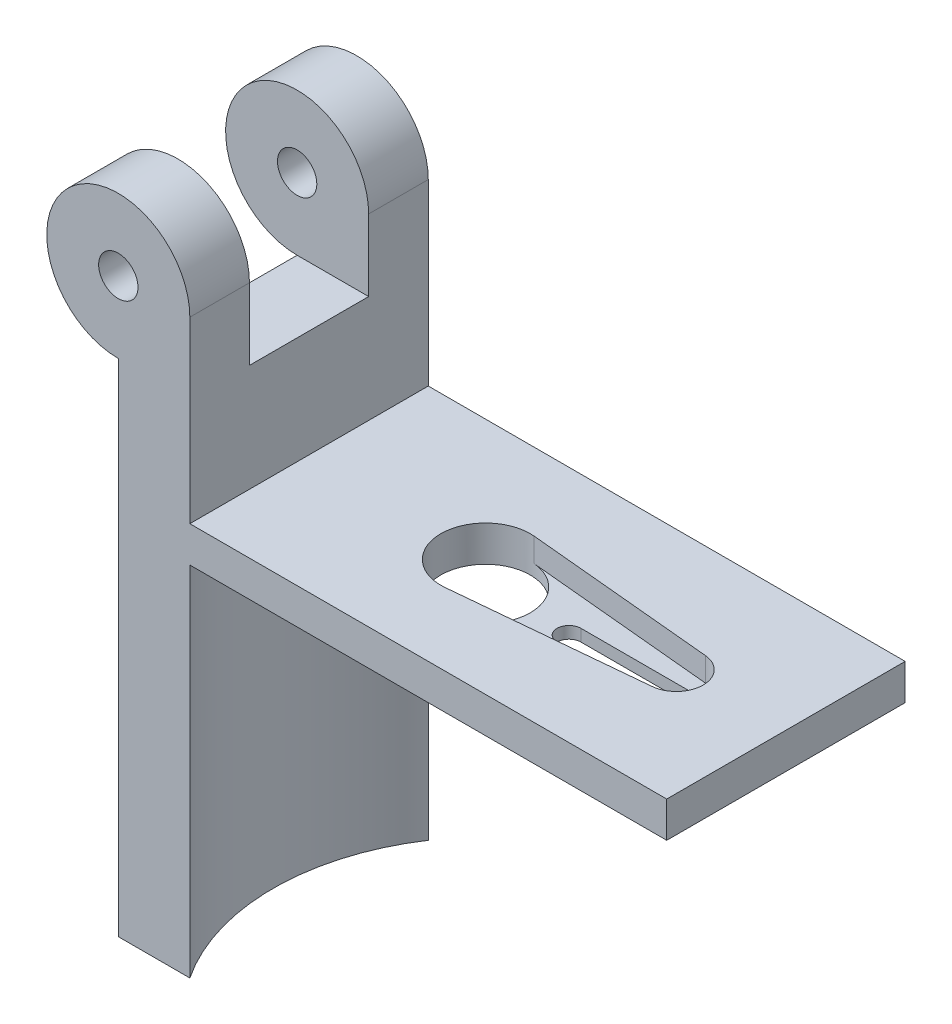
SolidWorks part; units mm, degrees
ref_plane "前视基准面" through (0, 0, 0) normal (0, 0, 1) x (1, 0, 0)
ref_plane "上视基准面" through (0, 0, 0) normal (0, 1, 0) x (1, 0, 0)
ref_plane "右视基准面" through (0, 0, 0) normal (1, 0, 0) x (0, 0, -1)
sketch "草图1" plane through (0, 0, 0) normal (0, 0, 1) x (1, 0, 0)
  line L1 (0, 0) -> (6, 0)
  line L2 (0, 0) -> (0, -48)
  line L3 (0, -48) -> (6, -48)
  line L4 (6, 0) -> (6, -48)
  line L5 (6, -15) -> (46, -15)
  line L6 (6, -15) -> (6, -18)
  line L7 (6, -18) -> (46, -18)
  line L8 (46, -15) -> (46, -18)
  circle A0 centre (0, 0) radius 1.65
  circle A1 centre (0, 0) radius 6
  dimension "D1" = 3.3
  dimension "D2" = 12
  dimension "D3" = 3
  dimension "D4" = 40
  dimension "D5" = 15
  dimension "D6" = 30
extrude "凸台-拉伸1" add sketch "草图1" along normal blind 20 contours L1 A1 L2 A0 | L2 A1 L1 A0 | A1 L2 L3 L4 | L8 L5 L4 L7
sketch "草图2" plane through (0, -15, 0) normal (0, 1, 0) x (1, 0, 0)
  line L0 (37.2109, -7.9566) -> (21.3516, -6.4632)
  line L1 (37.2109, -12.4368) -> (21.3516, -13.9302)
  line L2 (6, -20) -> (6, 0) construction
  circle A0 centre (37, -10.1967) radius 2.25
  circle A1 centre (21, -10.1967) radius 3.75
  point P8 (26.7105, -11.1863)
  point P9 (28.0646, -10.1967)
  dimension "D1" = 4.5
  dimension "D2" = 7.5
  dimension "D3" = 16
  dimension "D4" = 15
extrude "切除-拉伸1" cut sketch "草图2" against normal blind 2 contours A1 L1 A0 L0 | A0
sketch "草图3" plane through (0, -15, 0) normal (0, 1, 0) x (1, 0, 0)
  circle A0 centre (21, -10.1967) radius 3.75
extrude "切除-拉伸2" cut sketch "草图3" against normal blind 3
sketch "草图4" plane through (0, -17, 0) normal (0, 1, 0) x (1, 0, 0)
  line L0 (28, -10.1967) -> (37, -10.1967) construction
  line L1 (28, -9.1967) -> (37, -9.1967)
  line L2 (28, -11.1967) -> (37, -11.1967)
  arc A0 (28, -9.1967) -> (28, -11.1967) centre (28, -10.1967) ccw
  arc A1 (37, -11.1967) -> (37, -9.1967) centre (37, -10.1967) ccw
  arc A2 (37.2109, -12.4368) -> (37.2109, -7.9566) centre (37, -10.1967) ccw construction
  point P2 (32.5, -10.1967)
  dimension "D1" = 2
  dimension "D2" = 9
extrude "切除-拉伸3" cut sketch "草图4" against normal blind 3
sketch "草图5" plane through (6, 0, 0) normal (1, 0, 0) x (0, 0, -1)
  line L0 (-20, 0) -> (0, 0) construction
  line L1 (-15, 6) -> (-5, 6)
  line L2 (-15, 6) -> (-15, -6)
  line L3 (-15, -6) -> (-5, -6)
  line L4 (-5, 6) -> (-5, -6)
  line L5 (-15, 6) -> (-5, -6) construction
  line L6 (-15, -6) -> (-5, 6) construction
  line L7 (0, 0) -> (0, -15) construction
  point P0 (-10, 0)
  dimension "D1" = 10
  dimension "D2" = 12
  dimension "D3" = 6
  dimension "D4" = 5
extrude "切除-拉伸4" cut sketch "草图5" against normal blind 12
sketch "草图6" plane through (0, -48, 0) normal (0, -1, 0) x (1, 0, 0)
  line L0 (6, 20) -> (6, 0)
  arc A0 (6, 20) -> (6, 0) centre (21.0576, 10) ccw
extrude "切除-拉伸5" cut sketch "草图6" against normal blind 30
